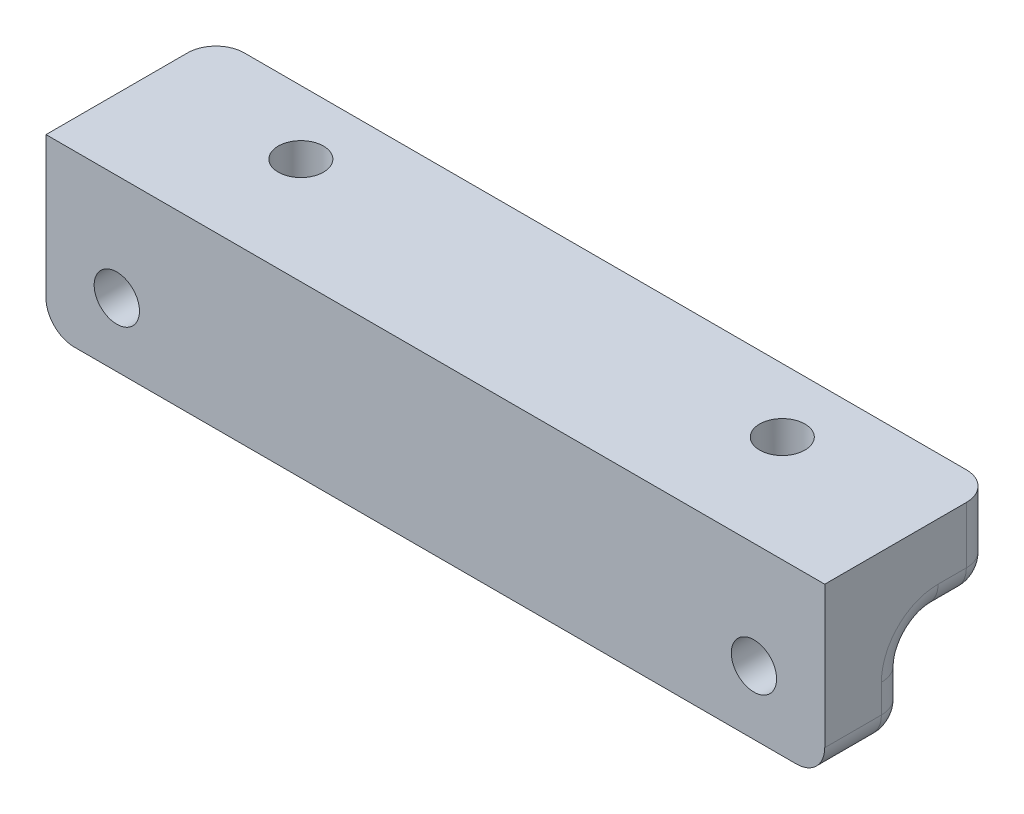
SolidWorks part; units mm, degrees
material "ABS"
ref_plane "Front" through (0, 0, 0) normal (0, 0, 1) x (1, 0, 0)
ref_plane "Top" through (0, 0, 0) normal (0, 1, 0) x (1, 0, 0)
ref_plane "Right" through (0, 0, 0) normal (1, 0, 0) x (0, 0, -1)
sketch "Esquisse1" plane through (0, 0, 0) normal (1, 0, 0) x (0, 0, -1)
  line L0 (12, 0) -> (0, 0)
  line L1 (0, 0) -> (0, -12)
  dimension "D1" = 90
  dimension "D2" = 12
  dimension "D3" = 12
extrude "Extru.-Mince1" add sketch "Esquisse1" along normal mid plane 55 thin thin type one direction reverse wall 6
fillet "Congé2" radius 2 3 edges at (0, -12, -6) (0, -6, -12) (0, -6, -6)
sketch "Esquisse2" plane through (0, 0, 0) normal (0, 1, 0) x (1, 0, 0)
  line L0 (0, -50) -> (0, 50) construction
  line L1 (27.5, 12) -> (-27.5, 12) construction
  line L2 (-27.5, 12) -> (-27.5, 0) construction
  circle A0 centre (-17, 7.5) radius 1.6
  circle A1 centre (17, 7.5) radius 1.6
  dimension "D1" = 34
  dimension "D2" = 4.5
  dimension "D3" = 3.2
  dimension "D4" = 10.5
extrude "Enlèv. mat.-Extru.1" cut sketch "Esquisse2" against normal through all
sketch "Esquisse3" plane through (0, 0, 0) normal (0, 0, 1) x (1, 0, 0)
  line L0 (27.5, -12) -> (-27.5, -12) construction
  line L1 (0, -50) -> (0, 50) construction
  circle A0 centre (22.5, -7.5) radius 1.6
  circle A1 centre (-22.5, -7.5) radius 1.6
  dimension "D1" = 4.5
  dimension "D2" = 3.2
  dimension "D3" = 45
extrude "Enlèv. mat.-Extru.2" cut sketch "Esquisse3" against normal through all
sketch "Esquisse4" plane through (0, 0, 0) normal (0, 1, 0) x (1, 0, 0)
  line L0 (27.5, 12) -> (-27.5, 12) construction
  line L1 (-14.25, 9.0877) -> (-17, 10.6754)
  line L2 (-17, 10.6754) -> (-19.75, 9.0877)
  line L3 (-19.75, 9.0877) -> (-19.75, 5.9123)
  line L4 (-19.75, 5.9123) -> (-17, 4.3246)
  line L5 (-17, 4.3246) -> (-14.25, 5.9123)
  line L6 (-14.25, 5.9123) -> (-14.25, 9.0877)
  line L7 (19.75, 9.0877) -> (17, 10.6754)
  line L8 (17, 10.6754) -> (14.25, 9.0877)
  line L9 (14.25, 9.0877) -> (14.25, 5.9123)
  line L10 (14.25, 5.9123) -> (17, 4.3246)
  line L11 (17, 4.3246) -> (19.75, 5.9123)
  line L12 (19.75, 5.9123) -> (19.75, 9.0877)
  circle A0 centre (-17, 7.5) radius 2.75 construction
  circle A1 centre (17, 7.5) radius 2.75 construction
  circle A2 centre (17, 7.5) radius 1.6 construction
  circle A3 centre (-17, 7.5) radius 1.6 construction
  dimension "D1" = 5.5
  dimension "D2" = 30
extrude "Enlèv. mat.-Extru.3" cut sketch "Esquisse4" against normal through all from offset 3 offset against normal yes
sketch "Esquisse5" plane through (0, 0, 0) normal (0, 0, 1) x (1, 0, 0)
  line L1 (25.25, -5.9123) -> (22.5, -4.3246)
  line L2 (22.5, -4.3246) -> (19.75, -5.9123)
  line L3 (19.75, -5.9123) -> (19.75, -9.0877)
  line L4 (19.75, -9.0877) -> (22.5, -10.6754)
  line L5 (22.5, -10.6754) -> (25.25, -9.0877)
  line L6 (25.25, -9.0877) -> (25.25, -5.9123)
  line L7 (-19.75, -9.0877) -> (-19.75, -5.9123)
  line L8 (-19.75, -5.9123) -> (-22.5, -4.3246)
  line L9 (-22.5, -4.3246) -> (-25.25, -5.9123)
  line L10 (-25.25, -5.9123) -> (-25.25, -9.0877)
  line L11 (-25.25, -9.0877) -> (-22.5, -10.6754)
  line L12 (-22.5, -10.6754) -> (-19.75, -9.0877)
  circle A0 centre (22.5, -7.5) radius 2.75 construction
  circle A1 centre (22.5, -7.5) radius 1.6 construction
  circle A2 centre (-22.5, -7.5) radius 2.75 construction
  dimension "D1" = 5.5
extrude "Enlèv. mat.-Extru.4" cut sketch "Esquisse5" against normal through all from offset 3 offset against normal yes
fillet "Congé1" radius 2 14 edges at (27.5, -2, -12) (-27.5, -2, -12) (27.5, -12, -2) (27.5, -11.4142, -5.4142) (27.5, -9, -6) (27.5, -6.5858, -6.5858) (27.5, -6, -9) (27.5, -5.4142, -11.4142) (-27.5, -12, -2) (-27.5, -11.4142, -5.4142) (-27.5, -9, -6) (-27.5, -6.5858, -6.5858) (-27.5, -6, -9) (-27.5, -5.4142, -11.4142)
sketch "Esquisse6" plane through (0, 0, 0) normal (0, 0, 1) x (1, 0, 0)
  line L4 (-25.5, -12) -> (25.5, -12)
  line L5 (27.5, -10) -> (27.5, 0)
  line L6 (27.5, 0) -> (-27.5, 0)
  line L7 (-27.5, 0) -> (-27.5, -10)
  line L8 (-25.5, -12) -> (25.5, -12)
  line L9 (27.5, -10) -> (27.5, 0)
  line L10 (27.5, 0) -> (-27.5, 0)
  line L11 (-27.5, 0) -> (-27.5, -10)
  arc A2 (25.5, -12) -> (27.5, -10) centre (25.5, -10) ccw
  arc A3 (-27.5, -10) -> (-25.5, -12) centre (-25.5, -10) ccw
  arc A4 (25.5, -12) -> (27.5, -10) centre (25.5, -10) ccw
  arc A5 (-27.5, -10) -> (-25.5, -12) centre (-25.5, -10) ccw
  dimension "D1" = 0
extrude "Boss.-Extru.1" [suppressed] add sketch "Esquisse6" against normal blind 0.2
